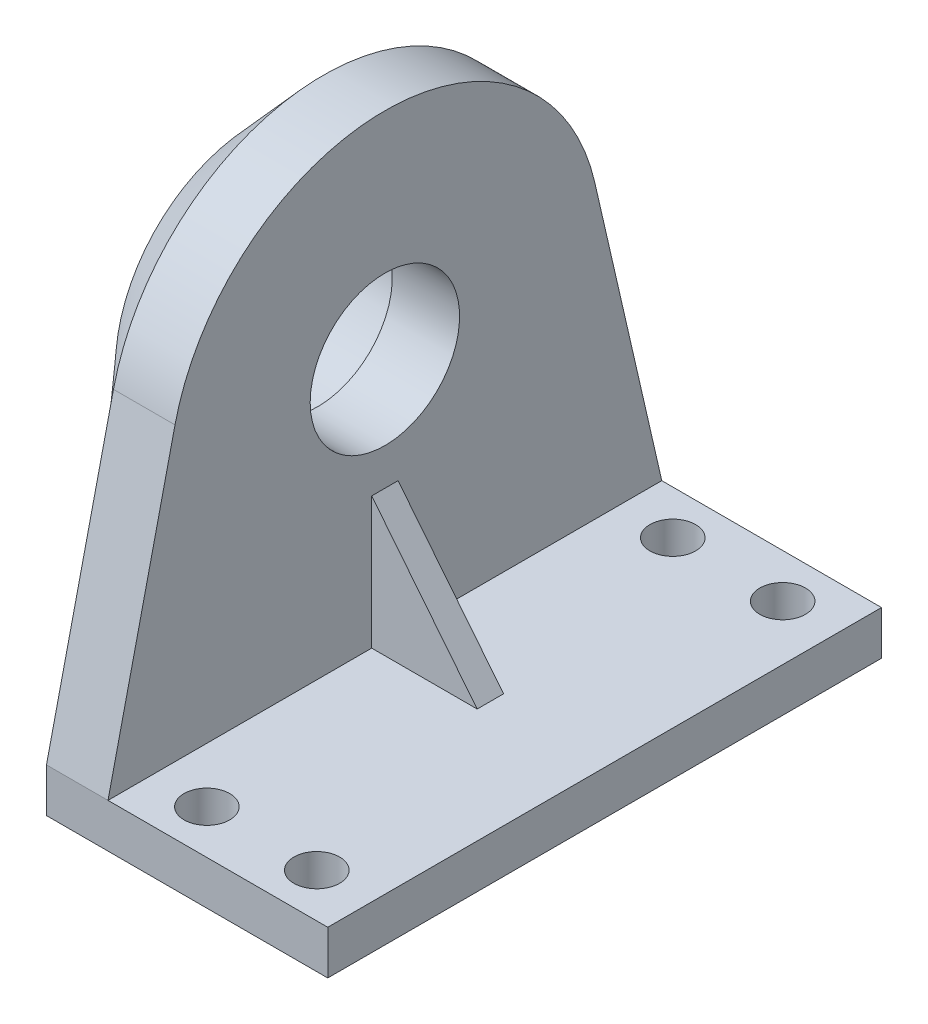
SolidWorks part; units mm, degrees
ref_plane "Front Plane" through (0, 0, 0) normal (0, 0, 1) x (1, 0, 0)
ref_plane "Top Plane" through (0, 0, 0) normal (0, 1, 0) x (1, 0, 0)
ref_plane "Right Plane" through (0, 0, 0) normal (1, 0, 0) x (0, 0, -1)
sketch "Sketch4" plane through (0, 0, 0) normal (0, 0, 1) x (1, 0, 0)
  line L0 (0, 0) -> (22.7302, 0) construction
  line L1 (0, 11) -> (7, 11)
  line L2 (0, 11) -> (0, 16)
  line L4 (7, 11) -> (7, 8.5)
  line L5 (7, 8.5) -> (14.6534, 8.5)
  line L6 (14.6534, 24.5) -> (14.6534, 8.5)
  line L7 (14.6534, 24.5) -> (7.6534, 24.5)
  line L8 (7.6534, 24.5) -> (0, 16)
  point P6 (33.1043, 29.6147)
  point P10 (35.6709, 24.2215)
  dimension "D1" = 11
  dimension "D2" = 7
  dimension "D3" = 2.5
  dimension "D4" = 5
  dimension "D5" = 42
  dimension "D6" = 7
  dimension "D7" = 16
revolve "Revolve1" add sketch "Sketch4" angle 360 about L0
sketch "Sketch5" plane through (14.6534, 0, 0) normal (1, 0, 0) x (0, 0, -1)
  line L0 (0, 0) -> (0, -32.7) construction
  line L3 (-31.5, -32.7) -> (31.5, -32.7)
  line L8 (-31.5, -32.7) -> (-31.5, -27.7)
  line L9 (-31.5, -27.7) -> (-23.8783, 5.4843)
  line L10 (31.5, -32.7) -> (31.5, -27.7)
  line L11 (31.5, -27.7) -> (23.8783, 5.4843)
  line L12 (31.5, -27.7) -> (-31.5, -27.7) construction
  circle A0 centre (0, 0) radius 24.5 construction
  circle A2 centre (0, 0) radius 24.5
  arc A3 (-23.8783, 5.4843) -> (23.8783, 5.4843) centre (0, 0) ccw
  point P7 (-30, -27.7)
  point P12 (-24.0266, 4.7929)
  dimension "D1" = 32.7
  dimension "D2" = 0
  dimension "D3" = 63
  dimension "D4" = 5
extrude "Boss-Extrude1" add sketch "Sketch5" against normal blind 7
sketch "Sketch6" plane through (14.6534, 0, 0) normal (1, 0, 0) x (0, 0, -1)
  line L0 (-31.5, -32.7) -> (31.5, -32.7) construction
  line L1 (31.5, -32.7) -> (-31.5, -32.7)
  line L2 (31.5, -32.7) -> (31.5, -27.7)
  line L3 (31.5, -27.7) -> (-31.5, -27.7)
  line L4 (-31.5, -32.7) -> (-31.5, -27.7)
  point P6 (0, 0)
  point P7 (24.5, -32.7)
  point P8 (0, 0)
  point P9 (0, 0)
  point P10 (0, 0)
  point P12 (-24.5, -27.7)
  point P13 (0, 0)
extrude "Boss-Extrude2" add sketch "Sketch6" along normal blind 25
sketch "Sketch7" plane through (0, -27.7, 0) normal (0, 1, 0) x (1, 0, 0)
  line L0 (14.6534, 0) -> (39.6534, 0) construction
  line L1 (33.4034, 26.5) -> (20.9034, 26.5) construction
  line L2 (33.4034, 26.5) -> (33.4034, -26.5) construction
  line L3 (33.4034, -26.5) -> (20.9034, -26.5) construction
  line L4 (20.9034, 26.5) -> (20.9034, -26.5) construction
  line L5 (39.6534, 31.5) -> (39.6534, -31.5) construction
  line L6 (14.6534, 31.5) -> (14.6534, -31.5) construction
  line L7 (27.1534, -31.5) -> (27.1534, 31.5) construction
  line L8 (39.6534, -31.5) -> (14.6534, -31.5) construction
  line L9 (39.6534, 31.5) -> (14.6534, 31.5) construction
  line L10 (27.1534, 26.5) -> (39.6534, 26.5) construction
  circle A0 centre (20.9034, 26.5) radius 2.6
  circle A1 centre (33.4034, 26.5) radius 2.6
  circle A2 centre (33.4034, -26.5) radius 2.6
  circle A3 centre (20.9034, -26.5) radius 2.6
  point P10 (20.9034, 0)
  point P21 (27.1534, 26.5)
  point P24 (33.4034, 26.5)
  dimension "D1" = 5.2
  dimension "D2" = 5.2
  dimension "D3" = 5.2
  dimension "D4" = 5.2
  dimension "D5" = 53
extrude "Cut-Extrude1" cut sketch "Sketch7" against normal through all
sketch "Sketch8" plane through (0, 0, 0) normal (0, 0, 1) x (1, 0, 0)
  line L0 (26.6534, -27.7) -> (14.6534, -12.7)
  line L1 (39.6534, -27.7) -> (14.6534, -27.7) construction
  line L2 (14.6534, 5.4843) -> (14.6534, -27.7) construction
  line L3 (23.5034, -27.7) -> (18.3034, -27.7) construction
  line L4 (14.6534, -8.5) -> (14.6534, 8.5) construction
  line L5 (26.6534, -27.7) -> (14.6534, -27.7)
  line L6 (14.6534, -27.7) -> (14.6534, -12.7)
  dimension "D1" = 15
  dimension "D2" = 12
extrude "Boss-Extrude3" add sketch "Sketch8" along normal mid plane 3
